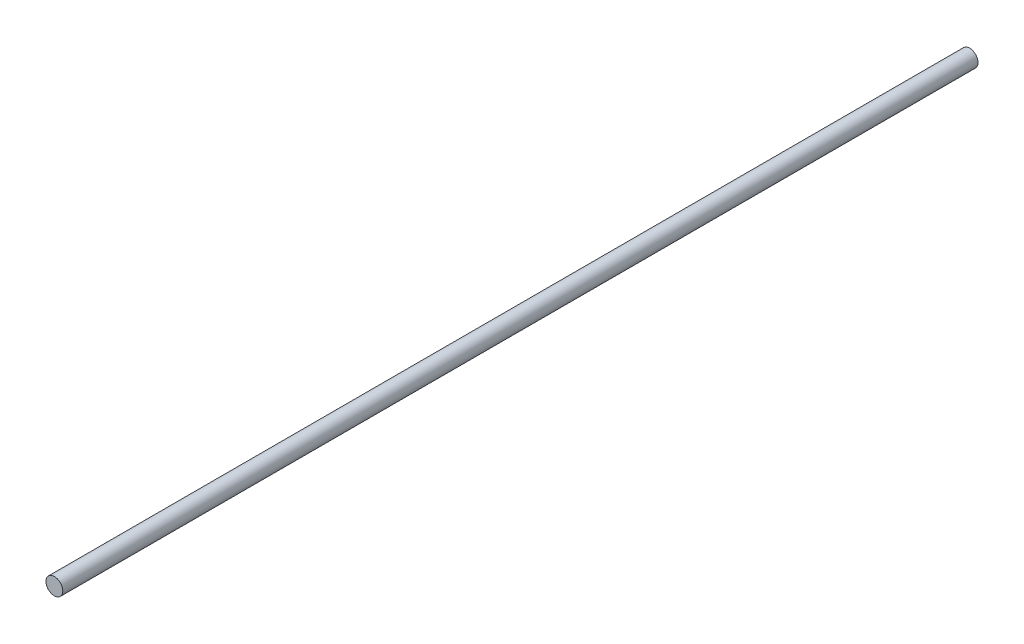
SolidWorks part; units mm, degrees
ref_plane "Front Plane" through (0, 0, 0) normal (0, 0, 1) x (1, 0, 0)
ref_plane "Top Plane" through (0, 0, 0) normal (0, 1, 0) x (1, 0, 0)
ref_plane "Right Plane" through (0, 0, 0) normal (1, 0, 0) x (0, 0, -1)
sketch "Sketch1" plane through (0, 0, 0) normal (0, 0, 1) x (1, 0, 0)
  circle A0 centre (0, 0) radius 4
  dimension "D1" = 8
extrude "Boss-Extrude1" add sketch "Sketch1" along normal blind 436
